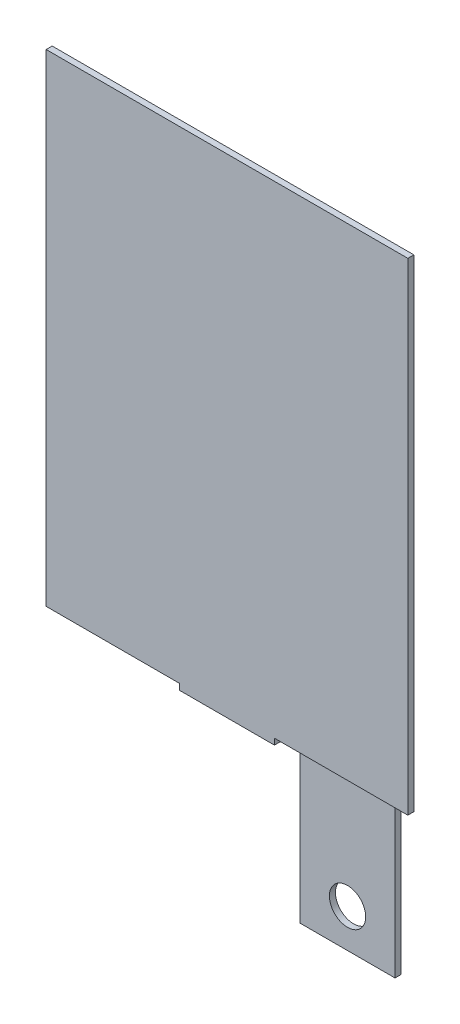
SolidWorks part; units mm, degrees
ref_plane "Front Plane" through (0, 0, 0) normal (0, 0, 1) x (1, 0, 0)
ref_plane "Top Plane" through (0, 0, 0) normal (0, 1, 0) x (1, 0, 0)
ref_plane "Right Plane" through (0, 0, 0) normal (1, 0, 0) x (0, 0, -1)
sketch "Sketch1" plane through (0, 0, 0) normal (0, 0, 1) x (1, 0, 0)
  line L0 (0, 130.048) -> (0, 98.298) construction
  line L1 (3.937, 107.823) -> (-3.937, 107.823)
  line L2 (3.937, 107.823) -> (3.937, 130.048)
  line L3 (3.937, 130.048) -> (-3.937, 130.048)
  line L4 (-3.937, 107.823) -> (-3.937, 130.048)
  line L5 (-3.937, 98.298) -> (-3.937, 130.048) construction
  line L6 (3.937, 130.048) -> (-3.937, 130.048) construction
  circle A0 centre (0, 123.698) radius 1.5045
  circle A1 centre (0, 110.998) radius 1.5045
  point P4 (0, 107.823)
  dimension "D1" = 3.175
extrude "Boss-Extrude1" add sketch "Sketch1" along normal blind 0.5
sketch "Sketch2" plane through (0, 0, 0.5) normal (0, 0, 1) x (1, 0, 0)
  line L0 (3.937, 107.823) -> (3.937, 130.048) construction
  line L1 (-3.937, 130.048) -> (3.937, 130.048)
  line L2 (-3.937, 130.048) -> (-3.937, 129.548)
  line L3 (-3.937, 129.548) -> (3.937, 129.548)
  line L4 (3.937, 130.048) -> (3.937, 129.548)
  dimension "D1" = 0.5
extrude "Boss-Extrude2" add sketch "Sketch2" along normal blind 10
sketch "Sketch3" plane through (0, 130.048, 0) normal (0, 1, 0) x (1, 0, 0)
  line L0 (-3.937, -10.5) -> (3.937, -10.5) construction
  line L1 (-15, -10.5) -> (15, -10.5)
  line L2 (-15, -10.5) -> (-15, -10)
  line L3 (-15, -10) -> (15, -10)
  line L4 (15, -10.5) -> (15, -10)
  point P4 (0, -10.5)
  dimension "D1" = 0.5
  dimension "D2" = 30
extrude "Boss-Extrude3" add sketch "Sketch3" along normal blind 40
